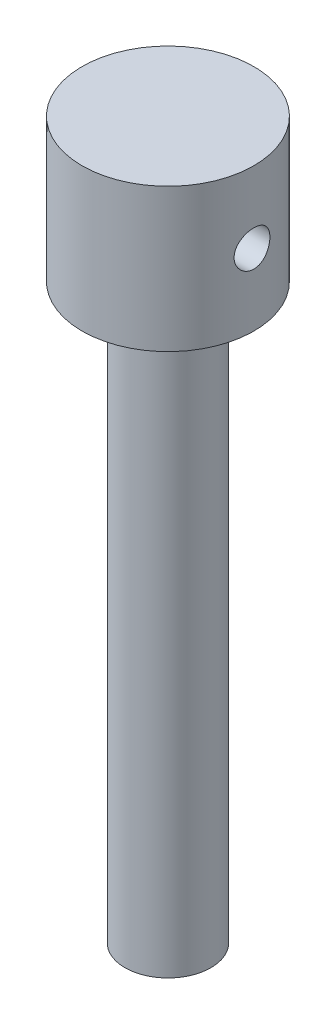
SolidWorks part; units mm, degrees
material "1060 Alloy"
ref_plane "Front Plane" through (0, 0, 0) normal (0, 0, 1) x (1, 0, 0)
ref_plane "Top Plane" through (0, 0, 0) normal (0, 1, 0) x (1, 0, 0)
ref_plane "Right Plane" through (0, 0, 0) normal (1, 0, 0) x (0, 0, -1)
sketch "Sketch2" plane through (0, 0, 0) normal (0, 1, 0) x (1, 0, 0)
  circle A0 centre (0, 0) radius 6
  dimension "D1" = 12
extrude "Boss-Extrude1" add sketch "Sketch2" along normal blind 80
sketch "Sketch3" plane through (0, 80, 0) normal (0, 1, 0) x (1, 0, 0)
  circle A0 centre (0, 0) radius 12
extrude "Boss-Extrude2" add sketch "Sketch3" along normal blind 20
sketch "Sketch4" plane through (0, 0, 0) normal (1, 0, 0) x (0, 0, -1)
  line L0 (0, 100) -> (0, 90) construction
  line L1 (12, 100) -> (-12, 100) construction
  circle A0 centre (0, 90) radius 2.5
  point P6 (0, 90)
extrude "Cut-Extrude1" cut sketch "Sketch4" against normal through all both and the other way through all
